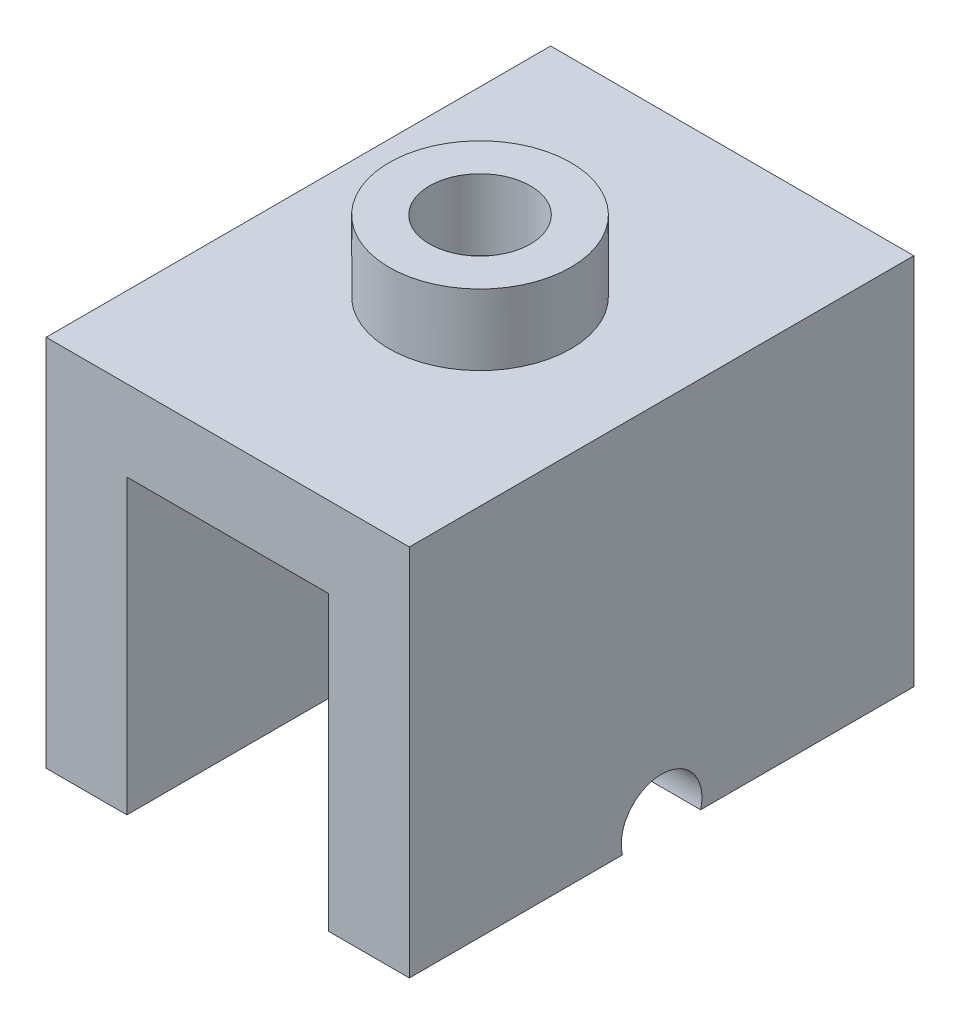
SolidWorks part; units mm, degrees
ref_plane "Front Plane" through (0, 0, 0) normal (0, 0, 1) x (1, 0, 0)
ref_plane "Top Plane" through (0, 0, 0) normal (0, 1, 0) x (1, 0, 0)
ref_plane "Right Plane" through (0, 0, 0) normal (1, 0, 0) x (0, 0, -1)
sketch "Sketch1" plane through (0, 0, 0) normal (0, 0, 1) x (1, 0, 0)
  line L0 (-9, 0) -> (9, 0)
  line L1 (9, 0) -> (9, -18.5)
  line L2 (9, -18.5) -> (5, -18.5)
  line L3 (5, -18.5) -> (5, -4)
  line L4 (5, -4) -> (-5, -4)
  line L5 (-5, -4) -> (-5, -18.5)
  line L6 (-5, -18.5) -> (-9, -18.5)
  line L7 (-9, -18.5) -> (-9, 0)
  line L8 (5, -4) -> (9, -4) construction
  line L9 (5, -4) -> (5, 0) construction
  point P7 (0, 0)
  dimension "D1" = 10
  dimension "D2" = 4
  dimension "D3" = 14.5
extrude "Boss-Extrude1" add sketch "Sketch1" along normal mid plane 25
sketch "Sketch2" plane through (0, 0, 0) normal (0, 1, 0) x (1, 0, 0)
  circle A0 centre (0, 0) radius 2.5
  dimension "D1" = 5
extrude "Extrude-Thin1" add sketch "Sketch2" along normal blind 3.5 thin
sketch "Sketch3" plane through (9, 0, 0) normal (1, 0, 0) x (0, 0, -1)
  line L1 (-12.5, -18.5) -> (12.5, -18.5) construction
  circle A0 centre (0, -18) radius 2
  point P2 (0, 0)
  dimension "D1" = 4
  dimension "D2" = 0.5
extrude "Cut-Extrude1" cut sketch "Sketch3" against normal up to surface (18 mm away) up to face at (-9, -9.25, 0)
